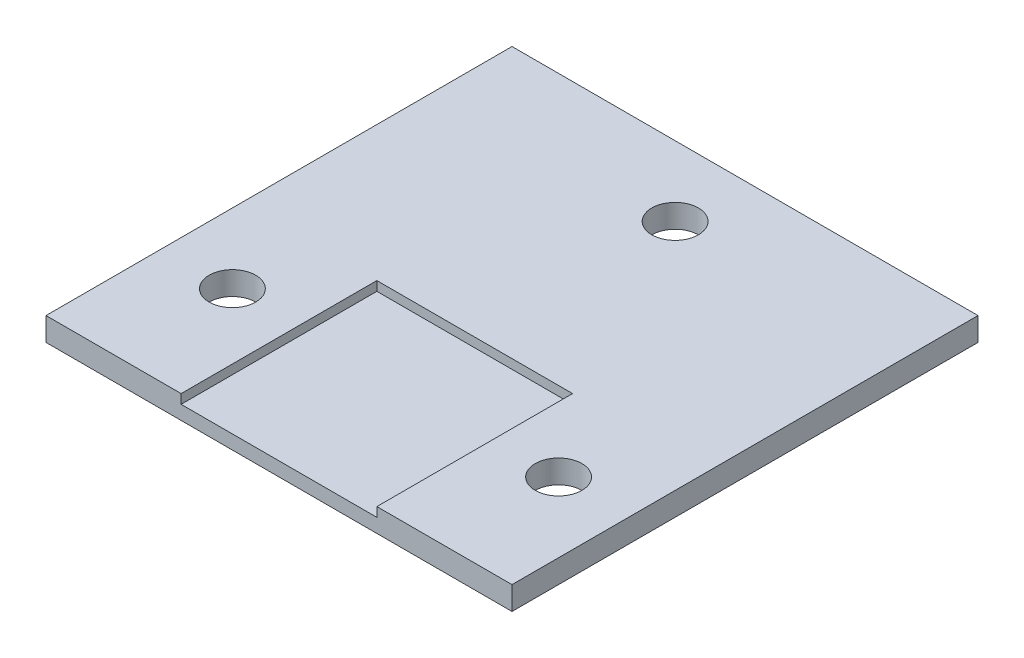
SolidWorks part; units mm, degrees
ref_plane "Front Plane" through (0, 0, 0) normal (0, 0, 1) x (1, 0, 0)
ref_plane "Top Plane" through (0, 0, 0) normal (0, 1, 0) x (1, 0, 0)
ref_plane "Right Plane" through (0, 0, 0) normal (1, 0, 0) x (0, 0, -1)
sketch "Sketch1" plane through (0, 0, 0) normal (0, 1, 0) x (1, 0, 0)
  line L1 (-50, -50) -> (50, -50)
  line L2 (-50, -50) -> (-50, 50)
  line L3 (-50, 50) -> (50, 50)
  line L4 (50, -50) -> (50, 50)
  line L5 (-50, -50) -> (50, 50) construction
  line L6 (-50, 50) -> (50, -50) construction
  point P0 (0, 0)
  point P6 (0, 0)
  dimension "D1" = 100
  dimension "D2" = 100
extrude "Boss-Extrude1" add sketch "Sketch1" along normal blind 5
sketch "Sketch2" plane through (0, 5, 0) normal (0, 1, 0) x (1, 0, 0)
  line L5 (-50, -50) -> (50, -50) construction
  line L7 (-21, -8) -> (21, -8)
  line L8 (-21, -8) -> (-21, -50)
  line L9 (-21, -50) -> (21, -50)
  line L10 (21, -8) -> (21, -50)
  line L11 (-21, -8) -> (21, -50) construction
  line L12 (-21, -50) -> (21, -8) construction
  dimension "D1" = 42
extrude "Cut-Extrude1" cut sketch "Sketch2" against normal blind 2
sketch "Sketch3" plane through (0, 5, 0) normal (0, 1, 0) x (1, 0, 0)
  line L0 (-50, -25) -> (50, -25)
  line L1 (-50, 50) -> (-50, -50) construction
  line L2 (50, -50) -> (50, 50) construction
  line L3 (-50, -50) -> (-21, -50) construction
  line L4 (0, 0) -> (0, 50)
  line L5 (50, 50) -> (-50, 50) construction
  circle A0 centre (-35, -25) radius 5
  circle A1 centre (35, -25) radius 5
  circle A2 centre (0, 35) radius 5
  dimension "D2" = 10
  dimension "D3" = 10
  dimension "D4" = 10
  dimension "D5" = 15
  dimension "D6" = 15
  dimension "D7" = 15
  dimension "D1" = 25
extrude "Cut-Extrude2" cut sketch "Sketch3" against normal blind 5 contours A2 | A1 | A0
